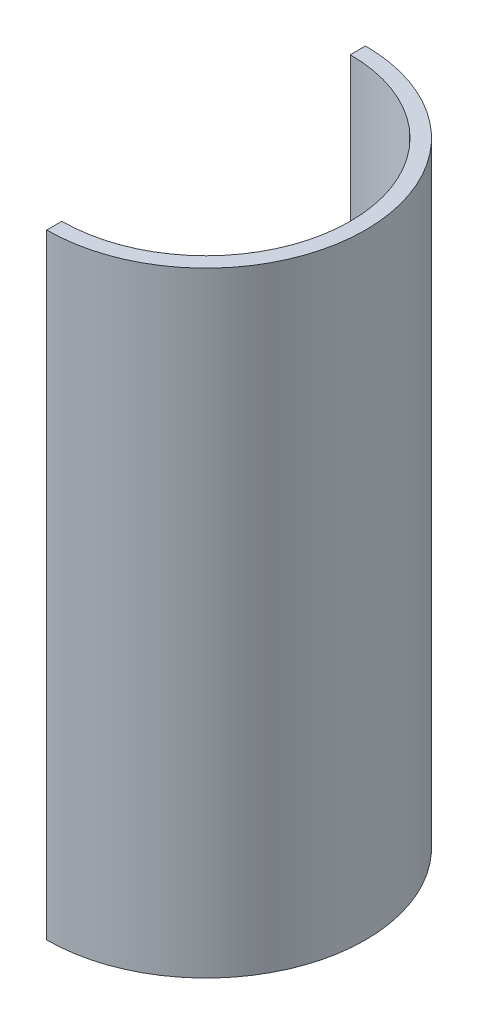
SolidWorks part; units mm, degrees
ref_plane "Front Plane" through (0, 0, 0) normal (0, 0, 1) x (1, 0, 0)
ref_plane "Top Plane" through (0, 0, 0) normal (0, 1, 0) x (1, 0, 0)
ref_plane "Right Plane" through (0, 0, 0) normal (1, 0, 0) x (0, 0, -1)
sketch "Sketch1" plane through (0, 0, 0) normal (0, 1, 0) x (1, 0, 0)
  circle A0 centre (0, 0) radius 10.5
extrude "Boss-Extrude1" add sketch "Sketch1" along normal blind 40.5
sketch "Sketch2" plane through (0, 0, 0) normal (1, 0, 0) x (0, 0, -1)
  line L1 (-17.8369, 48.8479) -> (23.4385, 48.8479)
  line L2 (-17.8369, 48.8479) -> (-17.8369, -1.7144)
  line L3 (-17.8369, -1.7144) -> (23.4385, -1.7144)
  line L4 (23.4385, 48.8479) -> (23.4385, -1.7144)
extrude "Cut-Extrude1" cut sketch "Sketch2" against normal blind 40.5
shell "Shell3" thickness 1
